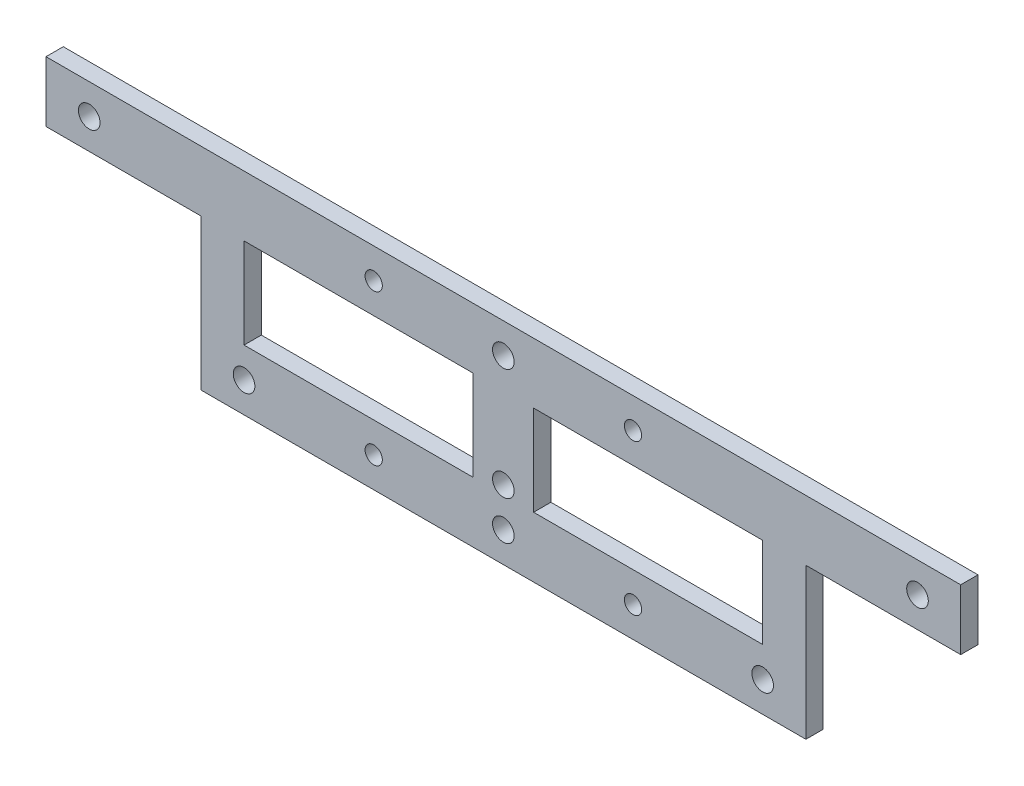
SolidWorks part; units mm, degrees
ref_plane "Front Plane" through (0, 0, 0) normal (0, 0, 1) x (1, 0, 0)
ref_plane "Top Plane" through (0, 0, 0) normal (0, 1, 0) x (1, 0, 0)
ref_plane "Right Plane" through (0, 0, 0) normal (1, 0, 0) x (0, 0, -1)
sketch "Sketch1" plane through (0, 0, 0) normal (0, 0, 1) x (1, 0, 0)
  line L0 (0, 0) -> (-60, 0) construction
  line L1 (0, 0) -> (60, 0) construction
  line L2 (0, 0) -> (-95.8264, 34.8779) construction
  line L3 (0, 0) -> (95.8264, 34.8779) construction
  line L4 (0, 41.8779) -> (0, 0) construction
  line L5 (-30, 34.8779) -> (30, 34.8779) construction
  line L6 (-70, 7) -> (70, 7)
  line L7 (-70, 7) -> (-70, -7)
  line L8 (-70, -7) -> (70, -7)
  line L9 (70, 7) -> (70, -7)
  line L10 (-7, 7) -> (7, 7)
  line L11 (-7, 7) -> (-7, 41.8779)
  line L12 (-7, 41.8779) -> (7, 41.8779)
  line L13 (7, 7) -> (7, 41.8779)
  line L14 (-105.8264, 27.8779) -> (-7, 27.8779)
  line L15 (-105.8264, 27.8779) -> (-105.8264, 41.8779)
  line L16 (-105.8264, 41.8779) -> (-7, 41.8779)
  line L17 (-7, 27.8779) -> (-7, 41.8779)
  line L18 (7, 41.8779) -> (105.8264, 41.8779)
  line L19 (7, 41.8779) -> (7, 27.8779)
  line L20 (7, 27.8779) -> (105.8264, 27.8779)
  line L21 (105.8264, 41.8779) -> (105.8264, 27.8779)
  line L22 (-70, 7) -> (-60, 7)
  line L23 (-70, 7) -> (-70, 27.8779)
  line L24 (-70, 27.8779) -> (-60, 27.8779)
  line L25 (-60, 7) -> (-60, 27.8779)
  line L26 (70, 7) -> (60, 7)
  line L27 (70, 7) -> (70, 27.8779)
  line L28 (70, 27.8779) -> (60, 27.8779)
  line L29 (60, 7) -> (60, 27.8779)
  circle A0 centre (-95.8264, 34.8779) radius 2.5
  circle A2 centre (95.8264, 34.8779) radius 2.5
  circle A3 centre (60, 0) radius 2.5
  circle A4 centre (0, 0) radius 2.5
  circle A5 centre (-60, 0) radius 2.5
  circle A6 centre (-30, 34.8779) radius 2
  circle A7 centre (30, 34.8779) radius 2
  circle A8 centre (-30, 0) radius 2
  circle A9 centre (30, 0) radius 2
  circle A10 centre (0, 34.8779) radius 2.5
  circle A12 centre (0, 9) radius 2.5
  dimension "D6" = 5
  dimension "D22" = 4
  dimension "D1" = 120
  dimension "D2" = 20
  dimension "D3" = 20
  dimension "D4" = 50
  dimension "D5" = 16
  dimension "D7" = 7
  dimension "D8" = 14
  dimension "D9" = 140
  dimension "D10" = 70
  dimension "D12" = 14
  dimension "D13" = 7
  dimension "D14" = 7
  dimension "D15" = 14
  dimension "D16" = 10
  dimension "D17" = 7
  dimension "D18" = 14
  dimension "D19" = 10
  dimension "D20" = 10
  dimension "D21" = 10
  dimension "D23" = 7
extrude "Boss-Extrude1" add sketch "Sketch1" along normal blind 4
